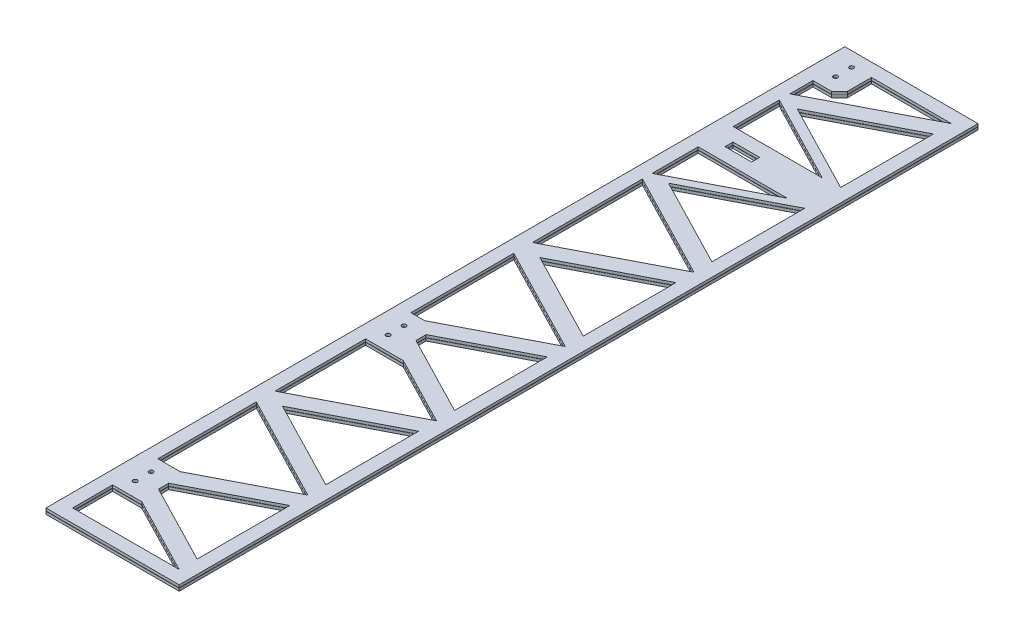
SolidWorks part; units mm, degrees
material "轻木"
ref_plane "前视基准面" through (0, 0, 0) normal (0, 0, 1) x (1, 0, 0)
ref_plane "上视基准面" through (0, 0, 0) normal (0, 1, 0) x (1, 0, 0)
ref_plane "右视基准面" through (0, 0, 0) normal (1, 0, 0) x (0, 0, -1)
other "Configuration Table"
sketch "草图2" plane through (0, 0, 762.01) normal (0, 0, 1) x (1, 0, 0)
  line L0 (130.7876, -3.3397) -> (130.7876, -3.4397) construction
  line L1 (130.7876, -2.3397) -> (180.7876, -2.3397)
  line L2 (130.7876, -2.3397) -> (130.7876, -3.3397)
  line L3 (130.7876, -3.3397) -> (180.7876, -3.3397)
  line L4 (180.7876, -2.3397) -> (180.7876, -3.3397)
  line L5 (130.7876, -3.4397) -> (180.7876, -3.4397)
  line L6 (130.7876, -3.4397) -> (130.7876, -4.4397)
  line L7 (130.7876, -4.4397) -> (180.7876, -4.4397)
  line L8 (180.7876, -3.4397) -> (180.7876, -4.4397)
  point P4 (130.7876, -3.3897)
  dimension "D1" = 1
  dimension "D2" = 50
  dimension "D3" = 1
  dimension "D4" = 50
  dimension "D5" = 0.1
extrude "凸台-拉伸1" add sketch "草图2" along normal blind 300
sketch "草图3" plane through (0, -2.3397, 0) normal (0, 1, 0) x (1, 0, 0)
  line L0 (175.7876, -1057.01) -> (175.7876, -767.01)
  line L1 (175.7876, -767.01) -> (135.7876, -767.01)
  line L2 (135.7876, -767.01) -> (135.7876, -1057.01)
  line L3 (135.7876, -1057.01) -> (175.7876, -1057.01)
  line L4 (180.7876, -762.01) -> (130.7876, -762.01)
  line L5 (130.7876, -762.01) -> (130.7876, -1062.01)
  line L6 (130.7876, -1062.01) -> (180.7876, -1062.01)
  line L7 (180.7876, -1062.01) -> (180.7876, -762.01)
  line L8 (180.7876, -762.01) -> (130.7876, -762.01)
  line L9 (130.7876, -762.01) -> (130.7876, -1062.01)
  line L10 (130.7876, -1062.01) -> (180.7876, -1062.01)
  line L11 (180.7876, -1062.01) -> (180.7876, -762.01)
  line L12 (180.7876, -912.01) -> (130.7876, -912.01) construction
  line L13 (175.7876, -1057.01) -> (135.7876, -1036.3433)
  line L14 (135.7876, -1029.3433) -> (175.7876, -1008.6767)
  line L15 (175.7876, -1008.6767) -> (135.7876, -988.01)
  line L16 (135.7876, -981.01) -> (175.7876, -960.3433)
  line L17 (175.7876, -960.3433) -> (135.7876, -939.6767)
  line L18 (135.7876, -932.6767) -> (175.7876, -912.01)
  line L19 (175.7876, -1050.2565) -> (142.0847, -1032.8433)
  line L20 (142.0847, -1032.8433) -> (175.7876, -1015.4302)
  line L21 (175.7876, -953.5898) -> (142.0847, -936.1767)
  line L22 (142.0847, -984.51) -> (175.7876, -967.0969)
  line L23 (142.0847, -936.1767) -> (163.3431, -925.1932) construction
  line L24 (142.0847, -936.1767) -> (175.7876, -918.7635)
  line L25 (129.0134, -936.1767) -> (160.5889, -919.8626) construction
  line L26 (178.5417, -1051.6794) -> (142.0847, -1032.8433) construction
  line L27 (175.7876, -1001.9231) -> (142.0847, -984.51)
  line L28 (188.8589, -1008.6767) -> (142.0847, -984.51) construction
  line L29 (188.8589, -960.3433) -> (142.0847, -936.1767) construction
  line L30 (142.0847, -1032.8433) -> (188.8589, -1008.6767) construction
  line L31 (175.7876, -960.3433) -> (129.0134, -936.1767) construction
  line L32 (142.0847, -984.51) -> (188.8589, -960.3433) construction
  line L33 (129.0134, -984.51) -> (175.7876, -960.3433) construction
  line L34 (175.7876, -1008.6767) -> (129.0134, -984.51) construction
  line L35 (129.0134, -1032.8433) -> (175.7876, -1008.6767) construction
  line L36 (175.7876, -1057.01) -> (129.0134, -1032.8433) construction
  line L37 (142.0847, -887.8433) -> (175.7876, -905.2565)
  line L38 (135.7876, -891.3433) -> (175.7876, -912.01)
  line L39 (175.7876, -870.4302) -> (142.0847, -887.8433)
  line L40 (175.7876, -863.6767) -> (135.7876, -884.3433)
  line L41 (135.7876, -843.01) -> (175.7876, -863.6767)
  line L42 (142.0847, -839.51) -> (175.7876, -856.9231)
  line L43 (175.7876, -822.0969) -> (142.0847, -839.51)
  line L44 (175.7876, -815.3433) -> (135.7876, -836.01)
  line L45 (135.7876, -794.6767) -> (175.7876, -815.3433)
  line L46 (175.7876, -767.01) -> (135.7876, -787.6767)
  line L47 (175.7876, -773.7635) -> (142.0847, -791.1767)
  line L48 (142.0847, -791.1767) -> (175.7876, -808.5898)
  line L49 (146.7553, -1042.01) -> (135.7876, -1042.01)
  line L50 (149.9811, -947.01) -> (135.7876, -947.01)
  line L51 (135.7876, -1025.01) -> (144.1747, -1025.01)
  line L52 (145.7876, -1030.9302) -> (145.7832, -1034.7542)
  line L53 (135.7876, -930.01) -> (140.9683, -930)
  line L54 (145.7876, -934.2635) -> (145.7876, -938.0898)
  line L55 (145.7876, -767.01) -> (145.7876, -776.01)
  line L56 (145.7876, -776.01) -> (142.7876, -779.01)
  line L57 (142.7876, -779.01) -> (135.7876, -779.01)
  dimension "D4" = 7
  dimension "D5" = 15
  dimension "D6" = 95
  dimension "D1" = 0
  dimension "D2" = 5
  dimension "D3" = 6
extrude "切除-拉伸1" cut sketch "草图3" against normal through all contours L46 L1 L2 | L47 L48 L0 | L41 L2 L40 | L0 L39 L37 | L38 L2 L18 | L24 L21 L0 | L16 L17 L2 | L27 L0 L22 | L14 L15 L2 | L20 L19 L0 | L3 L13 L2 | L0 L43 L42
sketch "草图4" plane through (0, -4.4397, 0) normal (0, -1, 0) x (1, 0, 0)
  line L0 (130.7876, 1062.01) -> (130.7876, 762.01) construction
  line L1 (140.7876, 817.01) -> (150.7876, 817.01)
  line L2 (140.7876, 817.01) -> (140.7876, 814.01)
  line L3 (140.7876, 814.01) -> (150.7876, 814.01)
  line L4 (150.7876, 817.01) -> (150.7876, 814.01)
  line L5 (130.7876, 762.01) -> (180.7876, 762.01) construction
  line L6 (175.7876, 822.0969) -> (135.7876, 822.0969)
  line L15 (135.7876, 822.0969) -> (135.7876, 839.3868)
  line L16 (169.2519, 822.0969) -> (135.7876, 839.3868)
  line L17 (175.7876, 822.0969) -> (142.0847, 839.51) construction
  line L18 (-849.2124, 815.51) -> (49150.7876, 815.51) construction
  line L19 (175.7876, 808.9231) -> (135.7876, 808.9231)
  line L20 (169.2519, 808.9231) -> (135.7876, 791.6332)
  line L21 (135.7876, 808.9231) -> (135.7876, 791.6332)
  point P23 (150.7876, 815.51)
  dimension "D1" = 10
  dimension "D2" = 3
  dimension "D3" = 10
  dimension "D4" = 52
  dimension "D5" = 3
  dimension "D6" = 40
extrude "切除-拉伸2" cut sketch "草图4" against normal blind 10 contours L18 L2 L3 L4 | L2 L18 L4 L1 | L19 L21 L20 | L6 L16 L15
sketch "草图5" plane through (0, -2.3397, 0) normal (0, 1, 0) x (1, 0, 0)
  line L0 (145.7876, -1030.9302) -> (145.7832, -1034.7542) construction
  line L1 (146.7553, -1042.01) -> (135.7876, -1042.01) construction
  line L2 (138.7812, -1036.4995) -> (124.7812, -1036.4995) construction
  line L3 (138.7812, -1036.4995) -> (138.7812, -1030.4995) construction
  line L4 (124.7812, -1030.4995) -> (124.7812, -935.4995) construction
  line L5 (124.7812, -935.4995) -> (124.7812, -767.4995) construction
  circle A0 centre (138.7812, -1036.4995) radius 0.8
  circle A1 centre (124.7812, -1036.4995) radius 0.8
  circle A2 centre (124.7812, -1030.4995) radius 0.8
  circle A3 centre (138.7812, -1030.4995) radius 0.8
  circle A4 centre (124.7812, -935.4995) radius 0.8
  circle A5 centre (138.7812, -935.4995) radius 0.8
  circle A6 centre (138.7812, -941.4995) radius 0.8
  circle A7 centre (124.7812, -941.4995) radius 0.8
  circle A8 centre (124.7812, -767.4995) radius 0.8
  circle A9 centre (138.7812, -767.4995) radius 0.8
  circle A10 centre (138.7812, -773.4995) radius 0.8
  circle A11 centre (124.7812, -773.4995) radius 0.8
  dimension "D1" = 1.6
  dimension "D2" = 7
  dimension "D3" = 5.5105
  dimension "D4" = 90
  dimension "D5" = 14
  dimension "D6" = 6
  dimension "D9" = 95
  dimension "D11" = 168
  dimension "D7" = 2
  dimension "D8" = 2
  dimension "D10" = 2
extrude "切除-拉伸3" cut sketch "草图5" against normal through all
